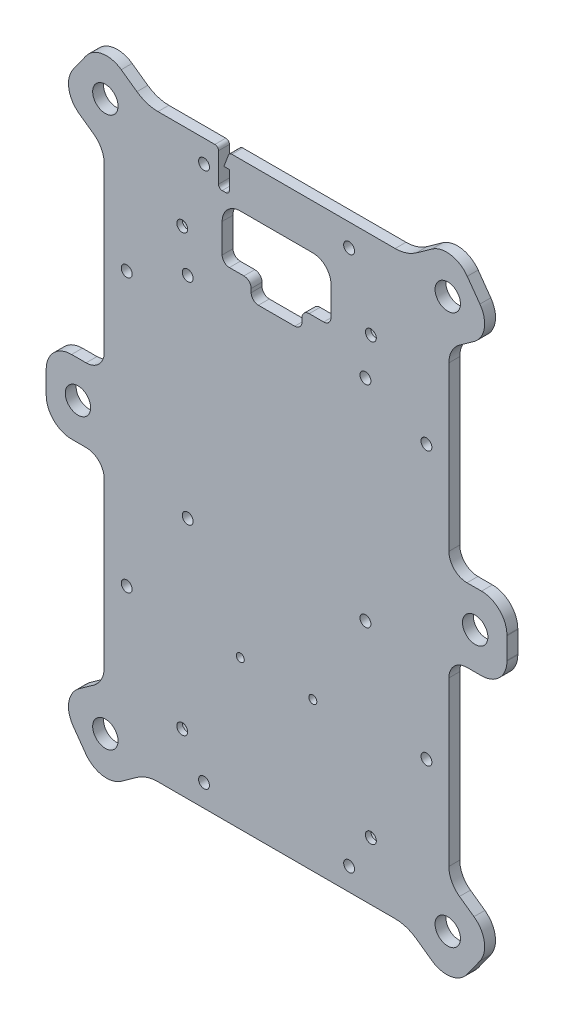
SolidWorks part; units mm, degrees
ref_plane "Front Plane" through (0, 0, 0) normal (0, 0, 1) x (1, 0, 0)
ref_plane "Top Plane" through (0, 0, 0) normal (0, 1, 0) x (1, 0, 0)
ref_plane "Right Plane" through (0, 0, 0) normal (1, 0, 0) x (0, 0, -1)
sketch "Sketch1" plane through (0, 0, 0) normal (0, 0, 1) x (1, 0, 0)
  line L0 (-10.5025, -18.172) -> (38.4975, -18.172) construction
  line L1 (-24.4982, 18.6863) -> (-28.8129, 21.7633)
  line L2 (-42.0602, 15.2434) -> (-38.5765, 20.1284)
  line L3 (-36.4405, 2.638) -> (-40.4254, 5.4798)
  line L4 (-33.5049, -3.0612) -> (-33.5049, -48.0612)
  line L5 (-42.5049, -53.0612) -> (-38.5049, -53.0612)
  line L6 (22.9975, -10.5612) -> (26.9975, -10.5612)
  line L7 (-49.5003, -60.2356) -> (-49.5003, -66.1084)
  line L8 (-49.5049, -60.0612) -> (-49.5003, -60.2356)
  line L9 (-2.0025, 15.828) -> (-2.0025, 7.828)
  line L10 (77.5, -60.0612) -> (77.4954, -60.2356)
  line L11 (77.4954, -60.2356) -> (77.4954, -66.1084)
  line L12 (70.5, -53.0612) -> (66.5, -53.0612)
  line L13 (61.5, -3.0612) -> (61.5, -48.0612)
  line L14 (64.4356, 2.638) -> (68.4204, 5.4798)
  line L15 (70.0553, 15.2434) -> (66.5716, 20.1284)
  line L16 (52.4933, 18.6863) -> (56.808, 21.7633)
  line L17 (20.9975, -12.5612) -> (20.9975, -13.5612)
  line L18 (52.4933, -145.0303) -> (56.808, -148.1073)
  line L19 (70.0553, -141.5874) -> (66.5716, -146.4724)
  line L20 (64.4356, -128.9821) -> (68.4204, -131.8238)
  line L21 (61.5, -123.2828) -> (61.5, -78.2828)
  line L22 (70.5, -73.2828) -> (66.5, -73.2828)
  line L23 (77.5, -66.2828) -> (77.4954, -66.1084)
  line L24 (46.6871, -143.172) -> (-18.692, -143.172)
  line L25 (-49.5049, -66.2828) -> (-49.5003, -66.1084)
  line L26 (-42.5049, -73.2828) -> (-38.5049, -73.2828)
  line L27 (-33.5049, -123.2828) -> (-33.5049, -78.2828)
  line L28 (-36.4405, -128.9821) -> (-40.4254, -131.8238)
  line L29 (-42.0602, -141.5874) -> (-38.5765, -146.4724)
  line L30 (-24.4982, -145.0303) -> (-28.8129, -148.1073)
  line L31 (18.9975, -15.5612) -> (8.9975, -15.5612)
  line L32 (6.9975, -13.5612) -> (6.9975, -12.5612)
  line L33 (4.9975, -10.5612) -> (0.9975, -10.5612)
  line L34 (13.9975, -76.172) -> (13.9975, -102.172) construction
  line L35 (3.9975, -102.172) -> (23.9975, -102.172) construction
  line L36 (-12.0025, -7.1838) -> (-12.0025, -127.1838) construction
  line L37 (-12.0025, -127.1838) -> (39.9975, -127.1838) construction
  line L38 (39.9975, -7.1838) -> (39.9975, -127.1838) construction
  line L39 (-6.0025, 10.6334) -> (-6.0025, 16.828) construction
  line L40 (-6.0025, 16.828) -> (-2.0025, 16.828) construction
  line L41 (-1.0025, 6.828) -> (-0.0025, 6.828)
  line L42 (0.9975, 7.828) -> (0.9975, 12.828)
  line L43 (1.6905, 16.828) -> (46.6871, 16.828)
  line L44 (-3.0025, 16.828) -> (-18.692, 16.828)
  line L45 (0.9975, 12.828) -> (-0.5025, 12.828)
  line L46 (-0.5025, 12.828) -> (0.7542, 16.1791)
  line L49 (38.4975, -18.172) -> (19.6579, -18.172) construction
  line L50 (13.9975, 16.828) -> (13.9975, -18.172) construction
  line L52 (28.9975, -8.5612) -> (28.9975, -0.5612)
  line L53 (23.9975, 4.4388) -> (3.9975, 4.4388)
  line L54 (-1.0025, -0.5612) -> (-1.0025, -8.5612)
  line L55 (-10.5025, -76.172) -> (38.4975, -76.172) construction
  line L56 (38.4975, -76.172) -> (19.6579, -76.172) construction
  line L57 (13.9975, -18.172) -> (13.9975, -76.172) construction
  line L58 (-12.0025, -7.1838) -> (39.9975, -7.1838) construction
  line L59 (39.9975, -7.1838) -> (18.1579, -7.1838) construction
  line L60 (13.9975, -7.1838) -> (13.9975, -18.172) construction
  circle A0 centre (68.7454, -63.172) radius 3.5
  circle A1 centre (-40.7503, -63.172) radius 3.5
  circle A2 centre (33.9975, 10.6334) radius 1.5
  arc A3 (-38.5049, -53.0612) -> (-33.5049, -48.0612) centre (-38.5049, -48.0612) ccw
  arc A4 (-49.5049, -60.0612) -> (-42.5049, -53.0612) centre (-42.5049, -60.0612) cw
  circle A5 centre (-6.0025, 10.6334) radius 1.5
  circle A6 centre (-33.1943, 12.6054) radius 3.5
  arc A7 (-24.4982, 18.6863) -> (-18.692, 16.828) centre (-18.692, 26.828) ccw
  arc A8 (-40.4254, 5.4798) -> (-42.0602, 15.2434) centre (-36.361, 11.179) cw
  arc A9 (-38.5765, 20.1284) -> (-28.8129, 21.7633) centre (-32.8773, 16.0641) cw
  arc A10 (-33.5049, -3.0612) -> (-36.4405, 2.638) centre (-40.5049, -3.0612) ccw
  arc A11 (61.5, -3.0612) -> (64.4356, 2.638) centre (68.5, -3.0612) cw
  arc A12 (66.5716, 20.1284) -> (56.808, 21.7633) centre (60.8724, 16.0641) ccw
  arc A13 (68.4204, 5.4798) -> (70.0553, 15.2434) centre (64.3561, 11.179) ccw
  arc A14 (52.4933, 18.6863) -> (46.6871, 16.828) centre (46.6871, 26.828) cw
  circle A15 centre (61.1894, 12.6054) radius 3.5
  circle A16 centre (-6.0025, -136.9774) radius 1.5
  arc A17 (77.5, -60.0612) -> (70.5, -53.0612) centre (70.5, -60.0612) ccw
  arc A18 (66.5, -53.0612) -> (61.5, -48.0612) centre (66.5, -48.0612) cw
  circle A19 centre (33.9975, -136.9774) radius 1.5
  circle A20 centre (-27.3149, -100.7828) radius 1.5
  circle A21 centre (55.31, -100.7828) radius 1.5
  circle A22 centre (-27.3149, -25.5612) radius 1.5
  circle A23 centre (55.31, -25.5612) radius 1.5
  circle A24 centre (-12.0025, -127.1838) radius 1.5
  arc A25 (66.5, -73.2828) -> (61.5, -78.2828) centre (66.5, -78.2828) ccw
  arc A26 (77.5, -66.2828) -> (70.5, -73.2828) centre (70.5, -66.2828) cw
  circle A27 centre (39.9975, -127.1838) radius 1.5
  circle A28 centre (61.1894, -138.9495) radius 3.5
  arc A29 (52.4933, -145.0303) -> (46.6871, -143.172) centre (46.6871, -153.172) ccw
  arc A30 (68.4204, -131.8238) -> (70.0553, -141.5874) centre (64.3561, -137.523) cw
  arc A31 (66.5716, -146.4724) -> (56.808, -148.1073) centre (60.8724, -142.4081) cw
  arc A32 (61.5, -123.2828) -> (64.4356, -128.9821) centre (68.5, -123.2828) ccw
  arc A33 (-33.5049, -123.2828) -> (-36.4405, -128.9821) centre (-40.5049, -123.2828) cw
  arc A34 (-38.5765, -146.4724) -> (-28.8129, -148.1073) centre (-32.8773, -142.4081) ccw
  arc A35 (-40.4254, -131.8238) -> (-42.0602, -141.5874) centre (-36.361, -137.523) ccw
  arc A36 (-24.4982, -145.0303) -> (-18.692, -143.172) centre (-18.692, -153.172) cw
  circle A37 centre (-33.1943, -138.9495) radius 3.5
  circle A38 centre (38.4975, -76.172) radius 1.5
  arc A39 (-49.5049, -66.2828) -> (-42.5049, -73.2828) centre (-42.5049, -66.2828) ccw
  arc A40 (-38.5049, -73.2828) -> (-33.5049, -78.2828) centre (-38.5049, -78.2828) cw
  circle A41 centre (-10.5025, -76.172) radius 1.5
  circle A42 centre (39.9975, -7.1838) radius 1.5
  circle A43 centre (-12.0025, -7.1838) radius 1.5
  arc A44 (22.9975, -10.5612) -> (20.9975, -12.5612) centre (22.9975, -12.5612) ccw
  arc A45 (6.9975, -12.5612) -> (4.9975, -10.5612) centre (4.9975, -12.5612) ccw
  arc A46 (20.9975, -13.5612) -> (18.9975, -15.5612) centre (18.9975, -13.5612) cw
  arc A47 (8.9975, -15.5612) -> (6.9975, -13.5612) centre (8.9975, -13.5612) cw
  circle A48 centre (3.9975, -102.172) radius 1.1
  circle A49 centre (23.9975, -102.172) radius 1.1
  circle A50 centre (38.4975, -18.172) radius 1.5
  circle A51 centre (-10.5025, -18.172) radius 1.5
  arc A52 (-2.0025, 7.828) -> (-1.0025, 6.828) centre (-1.0025, 7.828) ccw
  arc A53 (-0.0025, 6.828) -> (0.9975, 7.828) centre (-0.0025, 7.828) ccw
  arc A54 (1.6905, 16.828) -> (0.7542, 16.1791) centre (1.6905, 15.828) ccw
  arc A55 (-3.0025, 16.828) -> (-2.0025, 15.828) centre (-3.0025, 15.828) cw
  arc A70 (3.9975, 4.4388) -> (-1.0025, -0.5612) centre (3.9975, -0.5612) ccw
  arc A71 (23.9975, 4.4388) -> (28.9975, -0.5612) centre (23.9975, -0.5612) cw
  arc A72 (28.9975, -8.5612) -> (26.9975, -10.5612) centre (26.9975, -8.5612) cw
  arc A73 (0.9975, -10.5612) -> (-1.0025, -8.5612) centre (0.9975, -8.5612) cw
  point P25 (-34.5122, 25.8276)
  point P29 (-34.5122, 25.8276)
  point P64 (62.5072, 25.8276)
  point P95 (62.5072, -152.1716)
  point P124 (-34.5122, -152.1716)
  point P131 (13.9975, -7.1838)
  point P149 (13.9975, -102.172)
  dimension "D6" = 2
  dimension "D7" = 2
  dimension "D10" = 5
  dimension "D11" = 2
  dimension "D1" = 10
  dimension "D2" = 7
  dimension "D3" = 7
  dimension "D4" = 5
  dimension "D5" = 7
  dimension "D8" = 1
extrude "Бобышка-Вытянуть1" add sketch "Sketch1" against normal blind 3
sketch "Эскиз1" plane through (0, 0, -3) normal (0, 0, -1) x (-1, 0, 0)
  line L1 (12.0025, -4.0838) -> (9.3178, -5.6338)
  line L2 (9.3178, -5.6338) -> (9.3178, -8.7338)
  line L3 (9.3178, -8.7338) -> (12.0025, -10.2838)
  line L4 (12.0025, -10.2838) -> (14.6871, -8.7338)
  line L5 (14.6871, -8.7338) -> (14.6871, -5.6338)
  line L6 (14.6871, -5.6338) -> (12.0025, -4.0838)
  line L13 (-39.9975, -4.0838) -> (-42.6822, -5.6338)
  line L14 (-42.6822, -5.6338) -> (-42.6822, -8.7338)
  line L15 (-42.6822, -8.7338) -> (-39.9975, -10.2838)
  line L16 (-39.9975, -10.2838) -> (-37.3129, -8.7338)
  line L17 (-37.3129, -8.7338) -> (-37.3129, -5.6338)
  line L18 (-37.3129, -5.6338) -> (-39.9975, -4.0838)
  line L19 (-39.9975, -130.2838) -> (-37.3129, -128.7338)
  line L20 (-37.3129, -128.7338) -> (-37.3129, -125.6338)
  line L21 (-37.3129, -125.6338) -> (-39.9975, -124.0838)
  line L22 (-39.9975, -124.0838) -> (-42.6822, -125.6338)
  line L23 (-42.6822, -125.6338) -> (-42.6822, -128.7338)
  line L24 (-42.6822, -128.7338) -> (-39.9975, -130.2838)
  line L25 (12.0025, -130.2838) -> (14.6871, -128.7338)
  line L26 (14.6871, -128.7338) -> (14.6871, -125.6338)
  line L27 (14.6871, -125.6338) -> (12.0025, -124.0838)
  line L28 (12.0025, -124.0838) -> (9.3178, -125.6338)
  line L29 (9.3178, -125.6338) -> (9.3178, -128.7338)
  line L30 (9.3178, -128.7338) -> (12.0025, -130.2838)
  circle A0 centre (12.0025, -7.1838) radius 2.6847 construction
  circle A1 centre (-39.9975, -7.1838) radius 2.6847 construction
  circle A2 centre (-39.9975, -127.1838) radius 2.6847 construction
  circle A3 centre (12.0025, -127.1838) radius 2.6847 construction
extrude "Вырез-Вытянуть1" cut sketch "Эскиз1" against normal blind 1.5
